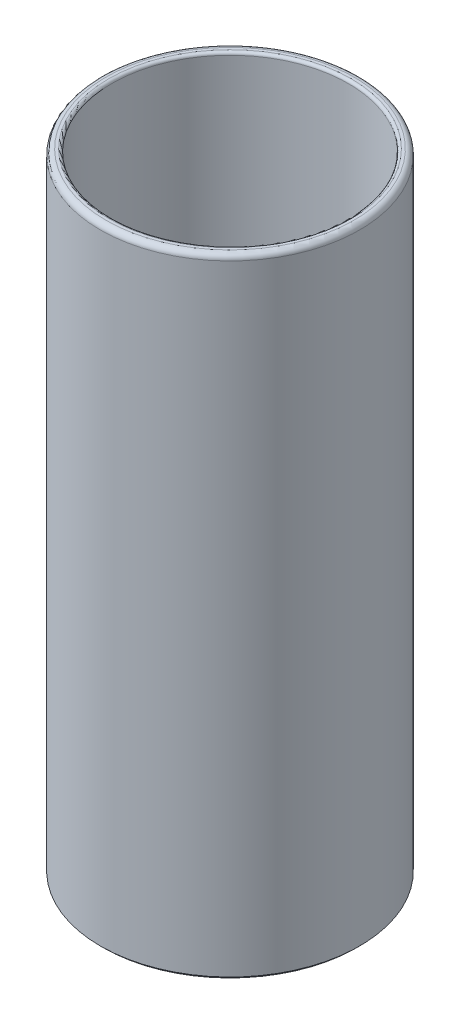
SolidWorks part; units mm, degrees
material "1060 Alloy"
ref_plane "Front Plane" through (0, 0, 0) normal (0, 0, 1) x (1, 0, 0)
ref_plane "Top Plane" through (0, 0, 0) normal (0, 1, 0) x (1, 0, 0)
ref_plane "Right Plane" through (0, 0, 0) normal (1, 0, 0) x (0, 0, -1)
sketch "Sketch1" plane through (0, 0, 0) normal (0, 1, 0) x (1, 0, 0)
  circle A0 centre (0, 0) radius 46.2
  dimension "D1" = 92.4
extrude "Boss-Extrude1" add sketch "Sketch1" along normal blind 224
shell "Shell1" thickness 4
fillet "Fillet1" radius 2 1 edges at (0, 4, 42.2)
fillet "Fillet2" radius 2 1 edges at (0, 224, 46.2)
fillet "Fillet3" radius 1 1 edges at (0, 224, 42.2)
chamfer "Chamfer1" distance 1 angle 45 1 edges at (0, 0, 46.2)
